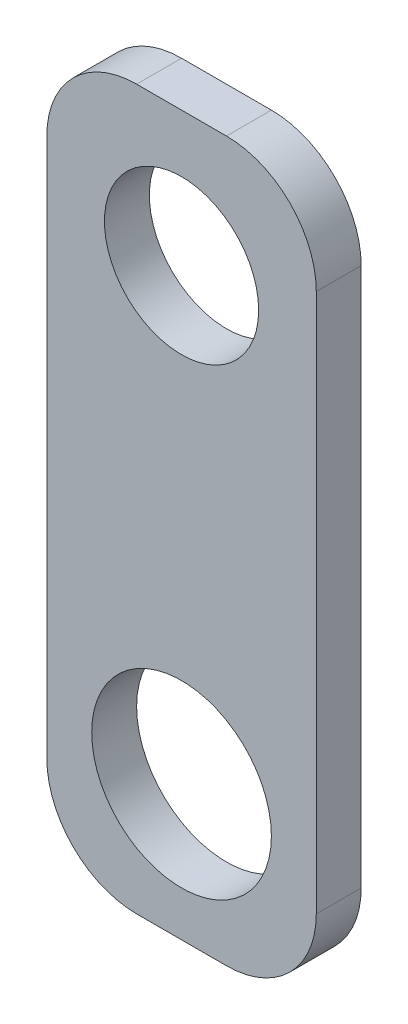
SolidWorks part; units mm, degrees
ref_plane "Front Plane" through (0, 0, 0) normal (0, 0, 1) x (1, 0, 0)
ref_plane "Top Plane" through (0, 0, 0) normal (0, 1, 0) x (1, 0, 0)
ref_plane "Right Plane" through (0, 0, 0) normal (1, 0, 0) x (0, 0, -1)
sketch "Sketch1" plane through (0, 0, 0) normal (0, 0, 1) x (1, 0, 0)
  line L1 (12.7, 0) -> (25.4, 0)
  line L2 (0, 12.7) -> (0, 88.9)
  line L3 (12.7, 101.6) -> (25.4, 101.6)
  line L4 (38.1, 12.7) -> (38.1, 88.9)
  line L5 (0, 50.8) -> (38.1, 50.8) construction
  line L6 (19.05, 19.05) -> (19.05, 82.55) construction
  circle A1 centre (19.05, 82.55) radius 10.903
  circle A2 centre (19.05, 19.05) radius 12.7
  arc A3 (12.7, 0) -> (0, 12.7) centre (12.7, 12.7) cw
  arc A4 (25.4, 0) -> (38.1, 12.7) centre (25.4, 12.7) ccw
  arc A5 (25.4, 101.6) -> (38.1, 88.9) centre (25.4, 88.9) cw
  arc A6 (0, 88.9) -> (12.7, 101.6) centre (12.7, 88.9) cw
  point P13 (19.05, 50.8)
  point P15 (0, 0)
  point P18 (38.1, 0)
  point P21 (38.1, 101.6)
  point P24 (0, 101.6)
  dimension "D1" = 21.8059
  dimension "D2" = 25.4
  dimension "D6" = 12.7
  dimension "D4" = 101.6
  dimension "D5" = 38.1
  dimension "D3" = 63.5
extrude "Boss-Extrude1" add sketch "Sketch1" along normal blind 6.35
equation "\"Hole_A\"= 0.8585"
equation "\"Hole_B\"= 1.0"
equation "\"L\"= 4'T"
equation "\"T\"= .25"
equation "\"W\"= 1.5"
equation "\"D4@Sketch1\"=\"L\""
equation "\"Hole_Spacing\"= 2.5"
equation "\"D3@Sketch1\"=\"Hole_Spacing\""
equation "\"D2@Sketch1\"=\"Hole_B\""
equation "\"D1@Sketch1\"=\"Hole_A\""
equation "\"D5@Sketch1\"=\"W\""
equation "\"D1@Boss-Extrude1\"=\"T\""
